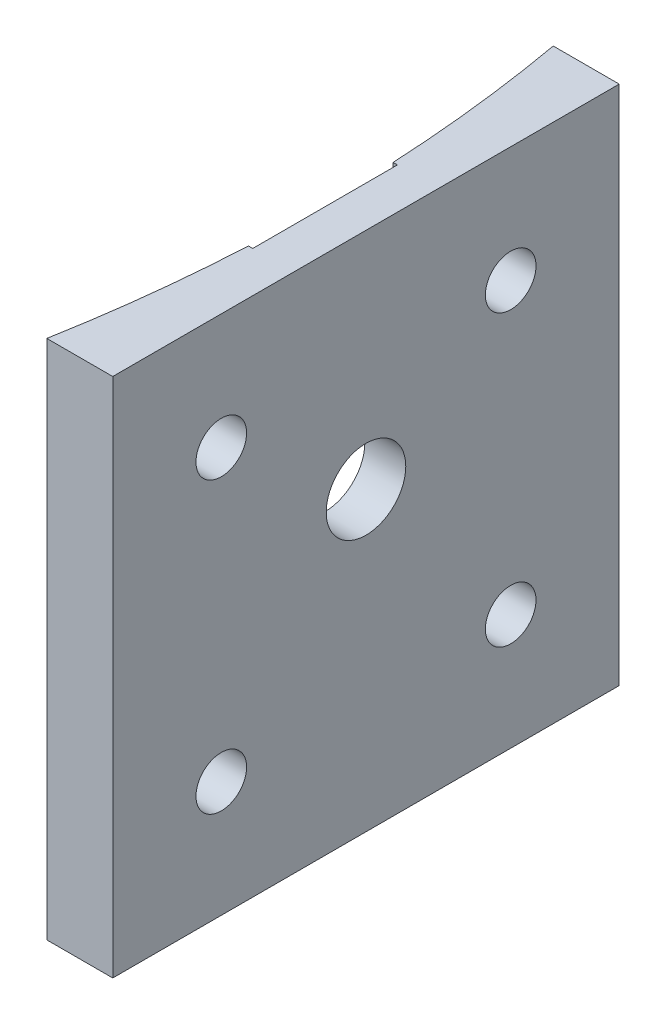
SolidWorks part; units mm, degrees
ref_plane "Спереди" through (0, 0, 0) normal (0, 0, 1) x (1, 0, 0)
ref_plane "Сверху" through (0, 0, 0) normal (0, 1, 0) x (1, 0, 0)
ref_plane "Справа" through (0, 0, 0) normal (1, 0, 0) x (0, 0, -1)
sketch "Эскиз1" plane through (0, 0, 0) normal (0, 1, 0) x (1, 0, 0)
  line L0 (-4.559, 17.5) -> (-4.559, -17.5) construction
  line L1 (0, 0) -> (-3, 0) construction
  line L2 (-4.559, 17.5) -> (0, 17.5)
  line L3 (0, 17.5) -> (0, -17.5)
  line L4 (0, -17.5) -> (-4.559, -17.5)
  arc A0 (-4.559, 17.5) -> (-4.559, -17.5) centre (-102, 0) cw
  dimension "D1" = 99
  dimension "D2" = 35
  dimension "D3" = 3
  dimension "D4" = 4.559
extrude "Бобышка-Вытянуть1" add sketch "Эскиз1" along normal blind 36
sketch "Эскиз2" plane through (0, 0, 0) normal (1, 0, 0) x (0, 0, -1)
  line L0 (0, 18) -> (0, 0) construction
  line L1 (-10, 28) -> (10, 28) construction
  line L2 (-10, 28) -> (-10, 8) construction
  line L3 (-10, 8) -> (10, 8) construction
  line L4 (10, 28) -> (10, 8) construction
  line L5 (-10, 28) -> (10, 8) construction
  line L6 (-10, 8) -> (10, 28) construction
  circle A0 centre (-10, 28) radius 1.75
  circle A1 centre (10, 28) radius 1.75
  circle A2 centre (10, 8) radius 1.75
  circle A3 centre (-10, 8) radius 1.75
  point P0 (0, 18)
  dimension "D4" = 3.5
  dimension "D5" = 3.5
  dimension "D6" = 3.5
  dimension "D7" = 3.5
  dimension "D1" = 18
  dimension "D2" = 20
  dimension "D3" = 20
extrude "Вырез-Вытянуть1" cut sketch "Эскиз2" against normal through all
sketch "Эскиз3" plane through (0, 36, 0) normal (0, 1, 0) x (1, 0, 0)
  line L1 (-2.8737, 5) -> (-3.1263, 5)
  line L2 (-2.8737, 5) -> (-2.8737, -5)
  line L3 (-2.8737, -5) -> (-3.1263, -5)
  line L4 (-3.1263, 5) -> (-3.1263, -5)
  line L5 (-2.8737, 5) -> (-3.1263, -5) construction
  line L6 (-2.8737, -5) -> (-3.1263, 5) construction
  arc A0 (-4.559, -17.5) -> (-4.559, 17.5) centre (-102, 0) ccw construction
  point P0 (-3, 0)
  point P8 (-3.1263, 5)
  dimension "D1" = 10
extrude "Бобышка-Вытянуть2" add sketch "Эскиз3" against normal through all
sketch "Эскиз4" plane through (0, 0, 0) normal (1, 0, 0) x (0, 0, -1)
  line L0 (0, 20.5) -> (0, 28) construction
  line L1 (-10, 28) -> (0, 28) construction
  line L2 (0, 28) -> (10, 28) construction
  circle A0 centre (0, 20.5) radius 2.75
  dimension "D2" = 5.5
  dimension "D1" = 7.5
extrude "Вырез-Вытянуть2" cut sketch "Эскиз4" against normal through all
sketch "Эскиз5" plane through (-3.1263, 0, 0) normal (-1, 0, 0) x (0, 0, 1)
  line L1 (5, 36) -> (-5, 36)
  line L2 (5, 36) -> (5, 0)
  line L3 (5, 0) -> (-5, 0)
  line L4 (-5, 36) -> (-5, 0)
extrude "Вырез-Вытянуть3" cut sketch "Эскиз5" against normal blind 0.3
